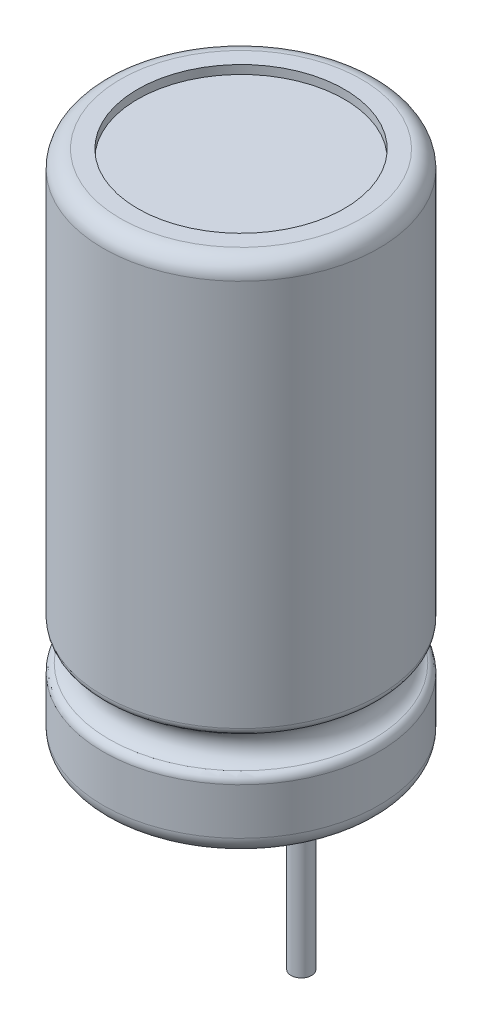
SolidWorks part; units mm, degrees
ref_plane "Front" through (0, 0, 0) normal (0, 0, 1) x (1, 0, 0)
ref_plane "Top" through (0, 0, 0) normal (0, 1, 0) x (1, 0, 0)
ref_plane "Right" through (0, 0, 0) normal (1, 0, 0) x (0, 0, -1)
sketch "Sketch1" plane through (0, 0, 0) normal (0, 1, 0) x (1, 0, 0)
  circle A0 centre (0, 0) radius 4
  dimension "D1" = 8
extrude "Base-Extrude" add sketch "Sketch1" along normal blind 15
sketch "Sketch2" plane through (0, 0, 0) normal (1, 0, 0) x (0, 0, -1)
  line L0 (-4, 15) -> (-4, 0) construction
  line L1 (-4, 3.0532) -> (-4, 2.0532)
  line L2 (0, 0) -> (0, 7.7627) construction
  line L3 (0, 15) -> (0, 0) construction
  arc A0 (-4, 2.0532) -> (-4, 3.0532) centre (-4, 2.5532) ccw
  dimension "D1" = 0.5
revolve "Cut-Revolve1" cut sketch "Sketch2" angle 360 about L2
fillet "Fillet1" radius 0.5 2 edges at (0, 0, 4) (0, 15, 4)
fillet "Fillet2" radius 0.25 2 edges at (0, 2.0532, -4) (0, 3.0532, -4)
sketch "Sketch4" plane through (0, 0, 0) normal (0, -1, 0) x (1, 0, 0)
  circle A0 centre (0, 0) radius 3
  dimension "D1" = 6
extrude "Cut-Extrude1" cut sketch "Sketch4" against normal blind 0.25
sketch "Sketch3" plane through (0, 0.25, 0) normal (0, -1, 0) x (1, 0, 0)
  circle A0 centre (-1.75, 0) radius 0.3
  circle A1 centre (1.75, 0) radius 0.3
  dimension "D1" = 0.6
  dimension "D2" = 1.75
  dimension "D3" = 3.5
extrude "Boss-Extrude1" add sketch "Sketch3" along normal blind 5
sketch "Sketch5" plane through (0, -4.75, 0) normal (0, -1, 0) x (1, 0, 0)
  circle A1 centre (-1.75, 0) radius 0.3
  circle A2 centre (-1.75, 0) radius 0.3
  dimension "D1" = 0
extrude "Cut-Extrude2" cut sketch "Sketch5" against normal blind 3
sketch "Sketch6" plane through (0, 15, 0) normal (0, 1, 0) x (-1, 0, 0)
  circle A0 centre (0, 0) radius 3
  dimension "D1" = 6
extrude "Cut-Extrude3" cut sketch "Sketch6" against normal blind 0.25
